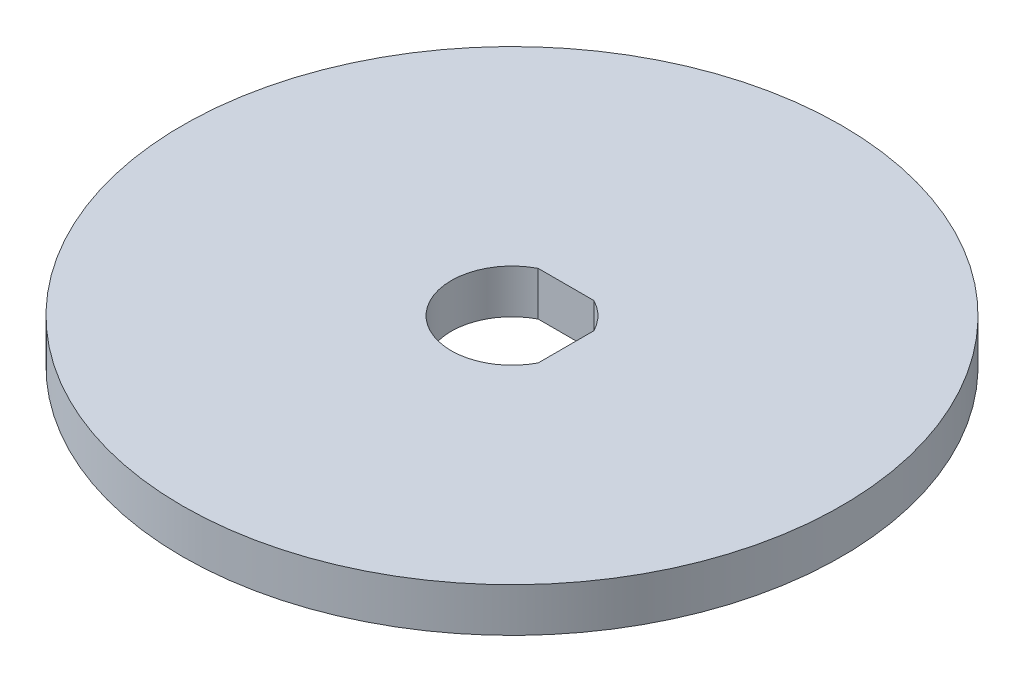
SolidWorks part; units mm, degrees
ref_plane "Спереди" through (0, 0, 0) normal (0, 0, 1) x (1, 0, 0)
ref_plane "Сверху" through (0, 0, 0) normal (0, 1, 0) x (1, 0, 0)
ref_plane "Справа" through (0, 0, 0) normal (1, 0, 0) x (0, 0, -1)
sketch "Эскиз1" plane through (0, 0, 0) normal (0, 1, 0) x (1, 0, 0)
  line L0 (1.9, 3.6895) -> (-1.9, 3.6895)
  line L1 (3.6895, 1.9) -> (3.6895, -1.9)
  circle A0 centre (0, 0) radius 22.5
  circle A1 centre (0, 0) radius 4.15 construction
  arc A2 (-1.9, 3.6895) -> (3.6895, -1.9) centre (0, 0) ccw
  arc A3 (1.9, 3.6895) -> (3.6895, 1.9) centre (0, 0) cw
  dimension "D1" = 45
  dimension "D2" = 8.3
  dimension "D3" = 3.8
extrude "Вытянуть1" add sketch "Эскиз1" along normal blind 3
sketch "Эскиз2" plane through (0, 0, 0) normal (0, -1, 0) x (1, 0, 0)
  circle A0 centre (0, 0) radius 12.5 construction
  circle A1 centre (0, 12.5) radius 1.4
  circle A2 centre (0, -12.5) radius 1.4
  dimension "D1" = 2.8
  dimension "D2" = 25
extrude "Вытянуть2" add sketch "Эскиз2" along normal blind 3
